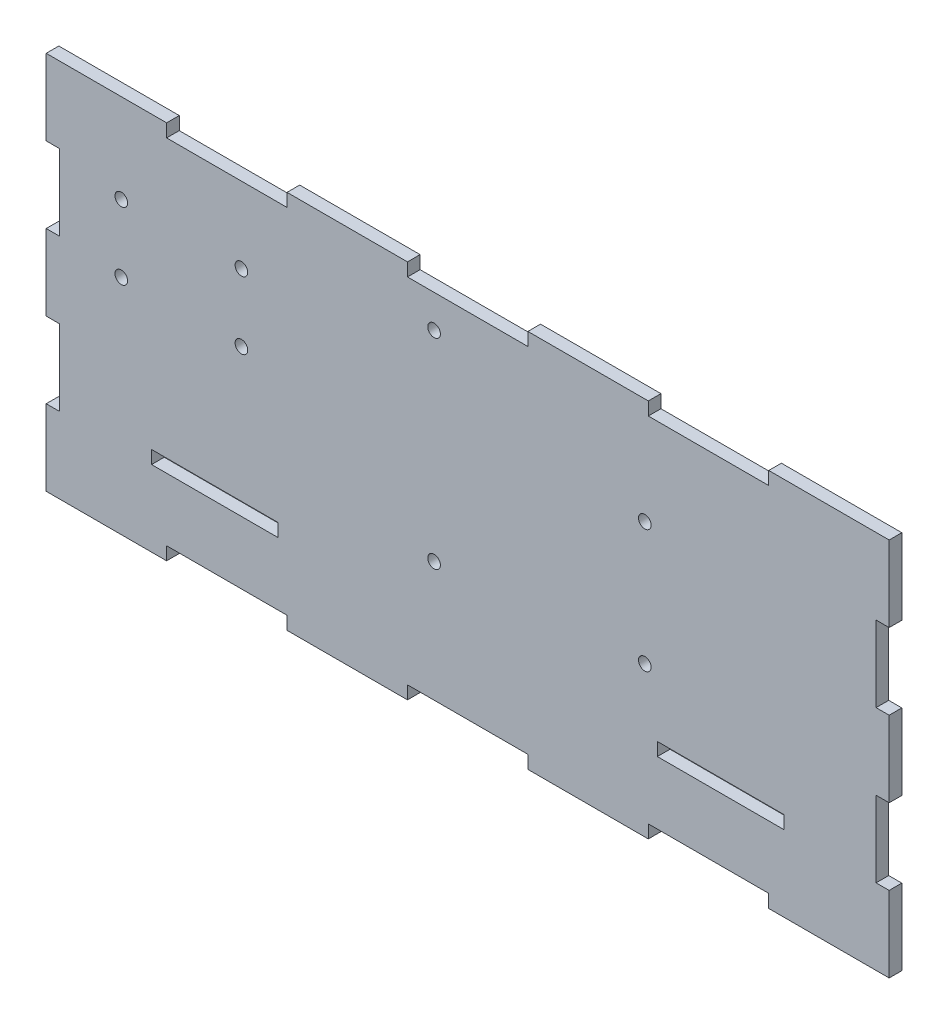
SolidWorks part; units mm, degrees
ref_plane "Alzado" through (0, 0, 0) normal (0, 0, 1) x (1, 0, 0)
ref_plane "Planta" through (0, 0, 0) normal (0, 1, 0) x (1, 0, 0)
ref_plane "Vista lateral" through (0, 0, 0) normal (1, 0, 0) x (0, 0, -1)
sketch "Croquis1" plane through (0, 0, 0) normal (0, 0, 1) x (1, 0, 0)
  line L0 (-100, 0) -> (100, 0) construction
  line L1 (-100, -45) -> (100, -45)
  line L2 (-100, -45) -> (-100, 45)
  line L3 (-100, 45) -> (100, 45)
  line L4 (100, -45) -> (100, 45)
  line L5 (-100, -45) -> (100, 45) construction
  line L6 (-100, 45) -> (100, -45) construction
  line L7 (-71.4286, 45) -> (-42.8571, 45)
  line L8 (-71.4286, 45) -> (-71.4286, 41.9)
  line L9 (-71.4286, 41.9) -> (-42.8571, 41.9)
  line L10 (-42.8571, 45) -> (-42.8571, 41.9)
  line L11 (-14.2857, 45) -> (14.2857, 45)
  line L12 (-14.2857, 45) -> (-14.2857, 41.9)
  line L13 (-14.2857, 41.9) -> (14.2857, 41.9)
  line L14 (14.2857, 45) -> (14.2857, 41.9)
  line L15 (42.8571, 45) -> (71.4286, 45)
  line L16 (42.8571, 45) -> (42.8571, 41.9)
  line L17 (42.8571, 41.9) -> (71.4286, 41.9)
  line L18 (71.4286, 45) -> (71.4286, 41.9)
  line L19 (-100, 27) -> (-96.9, 27)
  line L20 (-100, 27) -> (-100, 9)
  line L21 (-100, 9) -> (-96.9, 9)
  line L22 (-96.9, 27) -> (-96.9, 9)
  line L23 (-100, -9) -> (-96.9, -9)
  line L24 (-100, -9) -> (-100, -27)
  line L25 (-100, -27) -> (-96.9, -27)
  line L26 (-96.9, -9) -> (-96.9, -27)
  line L27 (0, 45) -> (0, -45) construction
  line L28 (100, -27) -> (96.9, -27)
  line L29 (96.9, -9) -> (96.9, -27)
  line L30 (100, -9) -> (96.9, -9)
  line L31 (100, -9) -> (100, -27)
  line L32 (100, 9) -> (96.9, 9)
  line L33 (96.9, 27) -> (96.9, 9)
  line L34 (100, 27) -> (96.9, 27)
  line L35 (100, 27) -> (100, 9)
  line L36 (71.4286, -45) -> (71.4286, -41.9)
  line L37 (42.8571, -41.9) -> (71.4286, -41.9)
  line L38 (42.8571, -45) -> (42.8571, -41.9)
  line L39 (14.2857, -45) -> (14.2857, -41.9)
  line L40 (-14.2857, -41.9) -> (14.2857, -41.9)
  line L41 (-14.2857, -45) -> (-14.2857, -41.9)
  line L42 (-42.8571, -45) -> (-42.8571, -41.9)
  line L43 (-71.4286, -41.9) -> (-42.8571, -41.9)
  line L44 (-71.4286, -45) -> (-71.4286, -41.9)
  point P0 (0, 0)
  point P26 (-98.45, 27)
  dimension "D1" = 200
  dimension "D2" = 90
  dimension "D3" = 28.5714
  dimension "D4" = 28.5714
  dimension "D5" = 28.5714
  dimension "D6" = 28.5714
  dimension "D7" = 28.5714
  dimension "D8" = 28.5714
  dimension "D9" = 28.5714
  dimension "D10" = 3.1
  dimension "D11" = 18
  dimension "D12" = 18
  dimension "D13" = 18
  dimension "D14" = 18
  dimension "D15" = 18
  dimension "D16" = 3.1
extrude "Saliente-Extruir1" add sketch "Croquis1" along normal mid plane 3 contours L34 L4 L3 L18 L17 L16 L14 L13 L12 L10 L9 L8 L2 L19 L22 L21 L23 L26 L25 L1 L28 L29 L30 L32 L33
sketch "Croquis2" plane through (0, 0, 1.5) normal (0, 0, 1) x (1, 0, 0)
  line L0 (-100, -45) -> (-71.4286, -45) construction
  line L1 (-75, -23.9) -> (-45, -23.9)
  line L2 (-75, -23.9) -> (-75, -27)
  line L3 (-75, -27) -> (-45, -27)
  line L4 (-45, -23.9) -> (-45, -27)
  line L5 (45, -23.9) -> (75, -23.9)
  line L6 (45, -23.9) -> (45, -27)
  line L7 (45, -27) -> (75, -27)
  line L8 (75, -23.9) -> (75, -27)
  line L9 (0, 41.9) -> (0, -45) construction
  line L10 (-14.2857, 41.9) -> (14.2857, 41.9) construction
  dimension "D1" = 30
  dimension "D2" = 3.1
  dimension "D3" = 18
  dimension "D4" = 45
  dimension "D5" = 30
extrude "Cortar-Extruir1" cut sketch "Croquis2" against normal blind 10
sketch "Croquis3" plane through (0, 0, 1.5) normal (0, 0, 1) x (1, 0, 0)
  circle A0 centre (-82.181, 23.8896) radius 1.5
  circle A1 centre (-53.681, 23.8896) radius 1.5
  circle A2 centre (-53.681, 7.8896) radius 1.5
  circle A3 centre (-82.181, 7.8896) radius 1.5
  point P8 (0, 0)
  dimension "D1" = 28.5
  dimension "D2" = 28.5
  dimension "D3" = 16
  dimension "D4" = 16
extrude "Cortar-Extruir2" cut sketch "Croquis3" against normal blind 3
sketch "Croquis6" plane through (0, 0, 1.5) normal (0, 0, 1) x (1, 0, 0)
  circle A0 centre (-7.9719, 34.0859) radius 1.5
  circle A1 centre (-7.9719, -13.4141) radius 1.5
  dimension "D1" = 47.5
extrude "Cortar-Extruir3" cut sketch "Croquis6" against normal blind 3
sketch "Croquis8" plane through (0, 0, 1.5) normal (0, 0, 1) x (1, 0, 0)
  line L0 (-7.9719, 34.0859) -> (-7.9719, -13.4141) construction
  line L1 (-7.9719, 34.0859) -> (63.8523, 34.0859) construction
  line L2 (-7.9719, -13.4141) -> (48.8774, -13.4141) construction
  circle A0 centre (42.0281, 19.7859) radius 1.5
  circle A1 centre (42.0281, -9.4141) radius 1.5
  dimension "D1" = 50
  dimension "D2" = 14.3
  dimension "D3" = 50
  dimension "D4" = 4
extrude "Cortar-Extruir4" cut sketch "Croquis8" against normal blind 3
